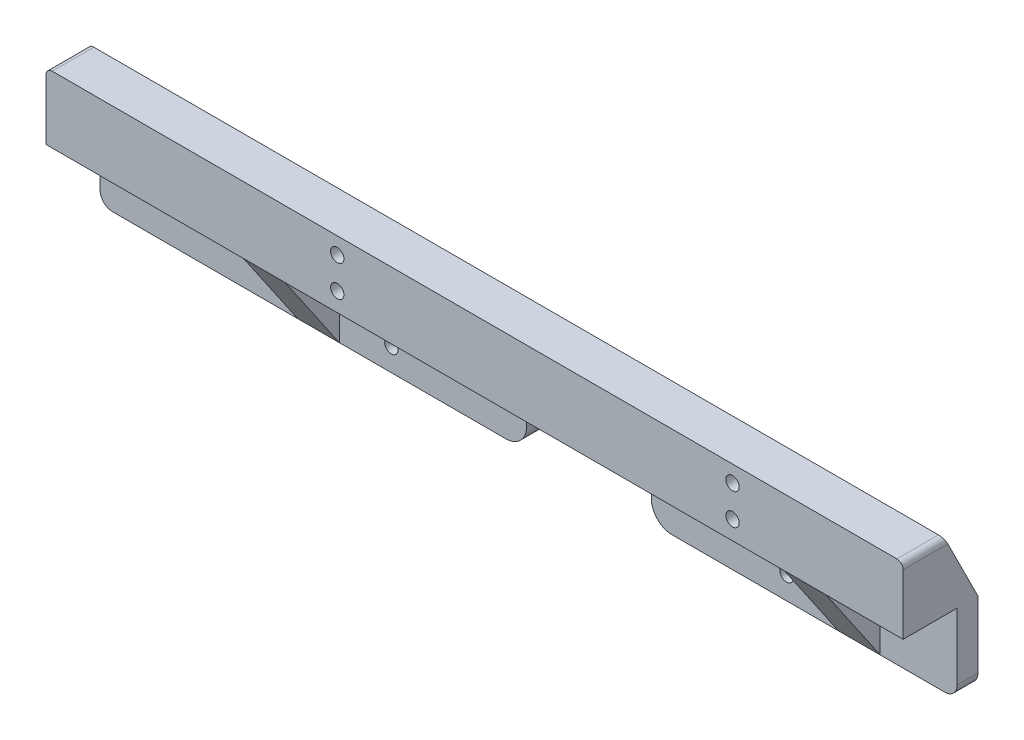
SolidWorks part; units mm, degrees
material "ABS"
ref_plane "前视基准面" through (0, 0, 0) normal (0, 0, 1) x (1, 0, 0)
ref_plane "上视基准面" through (0, 0, 0) normal (0, 1, 0) x (1, 0, 0)
ref_plane "右视基准面" through (0, 0, 0) normal (1, 0, 0) x (0, 0, -1)
sketch "草图1" plane through (0, 0, 0) normal (0, 0, 1) x (1, 0, 0)
  line L1 (-117.5, 17.5) -> (117.5, 17.5)
  line L2 (-117.5, 17.5) -> (-117.5, -17.5)
  line L3 (-117.5, -17.5) -> (117.5, -17.5)
  line L4 (117.5, 17.5) -> (117.5, -17.5)
  line L5 (0, -17.5) -> (0, 17.5) construction
  line L6 (-117.5, 0) -> (117.5, 0) construction
  circle A1 centre (-47.5, 13.5) radius 1.6
  circle A2 centre (47.5, 13.5) radius 1.6
  circle A3 centre (-47.5, 6) radius 1.6
  circle A4 centre (47.5, 6) radius 1.6
  point P0 (0, 0)
  dimension "D1" = 95
  dimension "D4" = 4
  dimension "D5" = 3.2
  dimension "D6" = 7.5
  dimension "D2" = 35
  dimension "D3" = 235
extrude "凸台-拉伸1" add sketch "草图1" along normal blind 18
fillet "圆角1" radius 1.5 2 edges at (117.5, 17.5, 9) (-117.5, 17.5, 9)
sketch "草图2" plane through (-117.5, 0, 0) normal (-1, 0, 0) x (0, 0, 1)
  line L0 (0, 1.5) -> (8, 17.5)
  line L1 (0, 16) -> (0, -17.5) construction
  line L2 (0, 17.5) -> (18, 17.5) construction
  line L3 (8, 17.5) -> (0, 17.5)
  line L4 (0, 17.5) -> (0, 1.5)
  dimension "D1" = 16
  dimension "D2" = 8
extrude "切除-拉伸1" cut sketch "草图2" against normal through all
sketch "草图3" plane through (-117.5, 0, 0) normal (-1, 0, 0) x (0, 0, 1)
  line L0 (5, 1.5) -> (0, 1.5) construction
  line L1 (5, 1.5) -> (18, 1.5)
  line L3 (5, 1.5) -> (5, -17.5)
  line L4 (5, -17.5) -> (18, -17.5)
  line L5 (18, 1.5) -> (18, -17.5)
  dimension "D1" = 13
extrude "切除-拉伸2" cut sketch "草图3" against normal through all
sketch "草图5" plane through (0, 0, 0) normal (0, 0, -1) x (-1, 0, 0)
  line L0 (0, 0) -> (0, -50.6933) construction
  line L1 (-117.5, 1.5) -> (117.5, 1.5) construction
  line L2 (47.5, -12) -> (47.5, -4.5) construction
  line L3 (-47.5, -12) -> (-47.5, -4.5) construction
  circle A0 centre (47.5, -4.5) radius 1.6
  circle A1 centre (47.5, -12) radius 1.6
  circle A2 centre (-47.5, -12) radius 1.6
  circle A3 centre (-47.5, -4.5) radius 1.6
  dimension "D1" = 3.2
  dimension "D2" = 95
  dimension "D3" = 6
  dimension "D4" = 7.5
extrude "切除-拉伸5" cut sketch "草图5" against normal through all
sketch "草图6" plane through (0, 0, 0) normal (0, 0, -1) x (-1, 0, 0)
  circle A0 centre (47.5, 6) radius 3
  circle A1 centre (47.5, 13.5) radius 3
  circle A2 centre (-47.5, 6) radius 3
  circle A3 centre (-47.5, 13.5) radius 3
  dimension "D1" = 6
extrude "切除-拉伸6" cut sketch "草图6" against normal blind 10
sketch "草图7" plane through (0, 0, 5) normal (0, 0, 1) x (1, 0, 0)
  line L0 (117.5, -17.5) -> (-117.5, -17.5) construction
  line L1 (35, -7.5) -> (-35, -7.5)
  line L2 (35, -7.5) -> (35, -17.5)
  line L3 (35, -17.5) -> (-35, -17.5)
  line L4 (-35, -7.5) -> (-35, -17.5)
  line L5 (0, -17.5) -> (0, -7.5) construction
  line L6 (35, -12.5) -> (-35, -12.5) construction
  point P0 (0, -12.5)
  dimension "D1" = 70
  dimension "D2" = 10
extrude "切除-拉伸7" [suppressed] cut sketch "草图7" against normal through all
sketch "草图10" plane through (0, 0, 0) normal (0, 0, -1) x (-1, 0, 0)
  line L6 (117.5, -17.5) -> (-117.5, -17.5) construction
  line L7 (-88.5, -17.5) -> (-117.5, -17.5)
  line L8 (-88.5, -17.5) -> (-88.5, 17.5)
  line L9 (-88.5, 17.5) -> (-117.5, 17.5)
  line L10 (-117.5, -17.5) -> (-117.5, 17.5)
  line L11 (-116, 17.5) -> (116, 17.5) construction
  line L12 (-117.5, -17.5) -> (-117.5, 1.5) construction
  dimension "D1" = 29
extrude "切除-拉伸9" cut sketch "草图10" against normal blind 30
fillet "圆角2" radius 3 2 edges at (-117.5, -17.5, 2.5) (88.5, -17.5, 2.5)
fillet "圆角5" radius 1.5 1 edges at (88.5, 17.5, 13)
sketch "草图11" plane through (0, 0, 0) normal (0, 0, -1) x (-1, 0, 0)
  line L0 (114.5, -17.5) -> (-85.5, -17.5) construction
  line L1 (-15, -17.5) -> (15, -17.5)
  line L2 (-15, -17.5) -> (-15, 1.5)
  line L3 (-15, 1.5) -> (15, 1.5)
  line L4 (15, -17.5) -> (15, 1.5)
  line L5 (-88.5, 1.5) -> (117.5, 1.5) construction
  point P9 (0, -17.5)
  dimension "D1" = 30
extrude "切除-拉伸10" cut sketch "草图11" against normal blind 30
fillet "圆角6" radius 5 4 edges at (15, -17.5, 2.5) (-15, -17.5, 2.5) (15, 1.5, 2.5) (-15, 1.5, 2.5)
ref_plane "基准面1" through (60, 0, 0) normal (1, 0, 0) x (0, 0, -1)
sketch "草图12" plane through (60, 0, 0) normal (1, 0, 0) x (0, 0, -1)
  line L0 (-18, 1.5) -> (-5, -17.5)
  line L1 (-5, -17.5) -> (-5, 1.5)
  line L2 (-5, 1.5) -> (-18, 1.5)
extrude "凸台-拉伸2" add sketch "草图12" along normal blind 10
mirror "镜向1" about plane through (0, 0, 0) normal (1, 0, 0) of "凸台-拉伸2"
ref_plane "基准面2" through (0, -25, 0) normal (0, 1, 0) x (1, 0, 0)
ref_plane "基准面3" through (0, 0, 28) normal (0, 0, 1) x (1, 0, 0)
